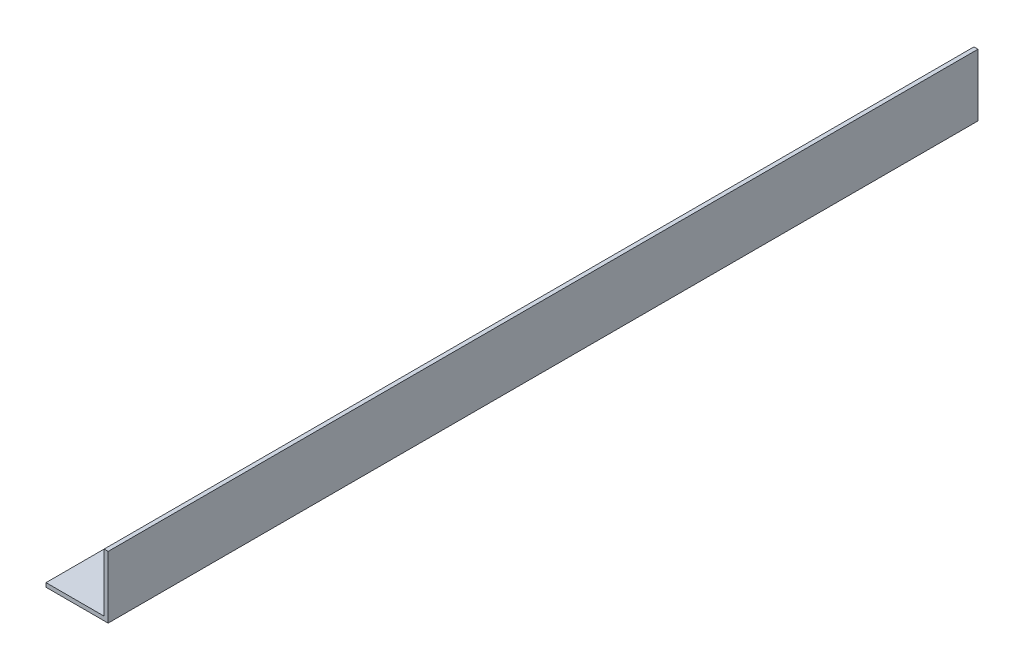
SolidWorks part; units mm, degrees
material "6061 Alloy"
ref_plane "Front Plane" through (0, 0, 0) normal (0, 0, 1) x (1, 0, 0)
ref_plane "Top Plane" through (0, 0, 0) normal (0, 1, 0) x (1, 0, 0)
ref_plane "Right Plane" through (0, 0, 0) normal (1, 0, 0) x (0, 0, -1)
sketch "Sketch1" plane through (0, 0, 0) normal (0, 0, 1) x (1, 0, 0)
  line L1 (-47.7896, 0) -> (-22.3896, 0)
  line L2 (-47.7896, 0) -> (-47.7896, -25.4)
  line L3 (-47.7896, -25.4) -> (-22.3896, -25.4)
  line L4 (-22.3896, 0) -> (-22.3896, -25.4)
  dimension "D1" = 25.4
  dimension "D2" = 25.4
extrude "Boss-Extrude1" add sketch "Sketch1" along normal blind 355.6
sketch "Sketch3" plane through (0, 0, 355.6) normal (0, 0, 1) x (1, 0, 0)
  line L1 (-50.2144, 2.729) -> (-24.0406, 2.729)
  line L2 (-50.2144, 2.729) -> (-50.2144, -23.749)
  line L3 (-50.2144, -23.749) -> (-24.0406, -23.749)
  line L4 (-24.0406, 2.729) -> (-24.0406, -23.749)
  line L5 (-50.2144, 2.729) -> (-24.0406, -23.749) construction
  line L6 (-50.2144, -23.749) -> (-24.0406, 2.729) construction
  line L8 (-22.3896, -25.4) -> (-22.3896, 0) construction
  line L9 (-47.7896, -25.4) -> (-22.3896, -25.4) construction
  point P0 (-37.1275, -10.51)
  dimension "D3" = 1.651
  dimension "D4" = 1.651
extrude "Cut-Extrude2" cut sketch "Sketch3" against normal blind 355.6
sketch "Sketch4" plane through (0, -25.4, 0) normal (0, -1, 0) x (1, 0, 0)
  line L0 (-47.7896, 355.6) -> (-22.3896, 355.6) construction
  circle A0 centre (-34.9453, 19.05) radius 3.556
  dimension "D1" = 7.112
  dimension "D2" = 336.55
extrude "Cut-Extrude3" cut sketch "Sketch4" against normal through all
